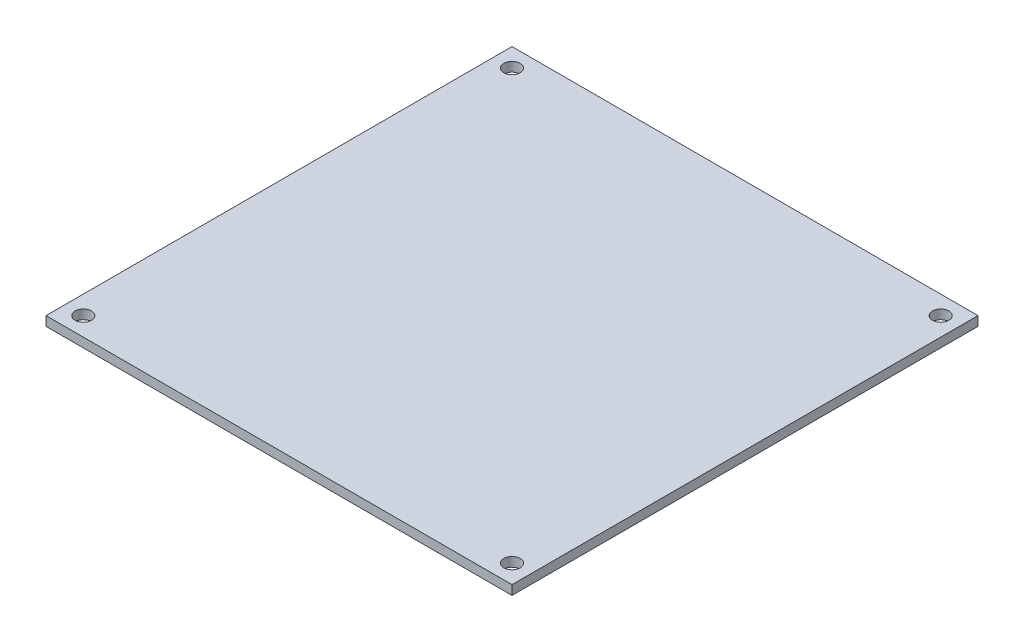
SolidWorks part; units mm, degrees
ref_plane "정면" through (0, 0, 0) normal (0, 0, 1) x (1, 0, 0)
ref_plane "윗면" through (0, 0, 0) normal (0, 1, 0) x (1, 0, 0)
ref_plane "우측면" through (0, 0, 0) normal (1, 0, 0) x (0, 0, -1)
sketch "스케치2" plane through (0, 0, 0) normal (0, 1, 0) x (1, 0, 0)
  line L0 (0, 50) -> (0, -50) construction
  line L5 (50, -50) -> (-50, -50)
  line L6 (50, -50) -> (50, 50)
  line L7 (50, 50) -> (-50, 50)
  line L8 (-50, -50) -> (-50, 50)
  line L9 (50, -50) -> (-50, 50) construction
  line L10 (50, 50) -> (-50, -50) construction
  line L11 (-50, 0) -> (50, 0) construction
  circle A0 centre (-46, 46) radius 1.75
  circle A1 centre (46, 46) radius 1.75
  circle A2 centre (46, -46) radius 1.75
  circle A3 centre (-46, -46) radius 1.75
  point P0 (0, 0)
  dimension "D3" = 3.5
  dimension "D1" = 100
  dimension "D2" = 100
  dimension "D4" = 4
  dimension "D5" = 4
extrude "보스-돌출1" add sketch "스케치2" along normal blind 2
